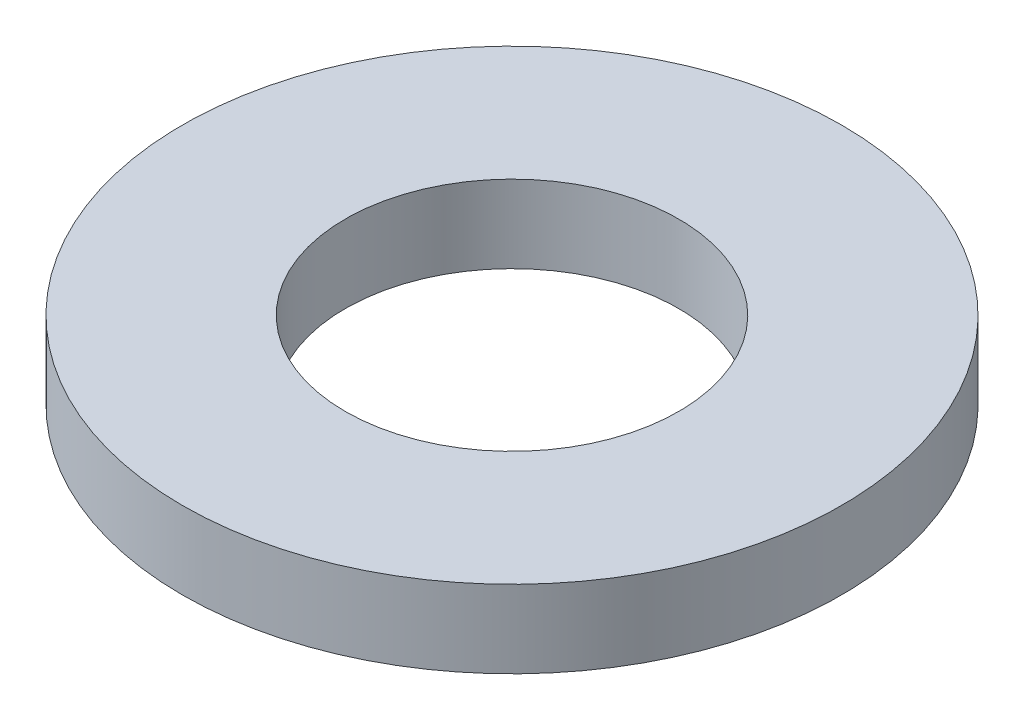
SolidWorks part; units mm, degrees
ref_plane "前视基准面" through (0, 0, 0) normal (0, 0, 1) x (1, 0, 0)
ref_plane "上视基准面" through (0, 0, 0) normal (0, 1, 0) x (1, 0, 0)
ref_plane "右视基准面" through (0, 0, 0) normal (1, 0, 0) x (0, 0, -1)
sketch "草图1" plane through (0, 0, 0) normal (0, 1, 0) x (1, 0, 0)
  circle A0 centre (0, 0) radius 2.15
  circle A1 centre (0, 0) radius 4.25
  dimension "D1" = 4.3
  dimension "D2" = 8.5
extrude "凸台-拉伸1" add sketch "草图1" along normal blind 1
